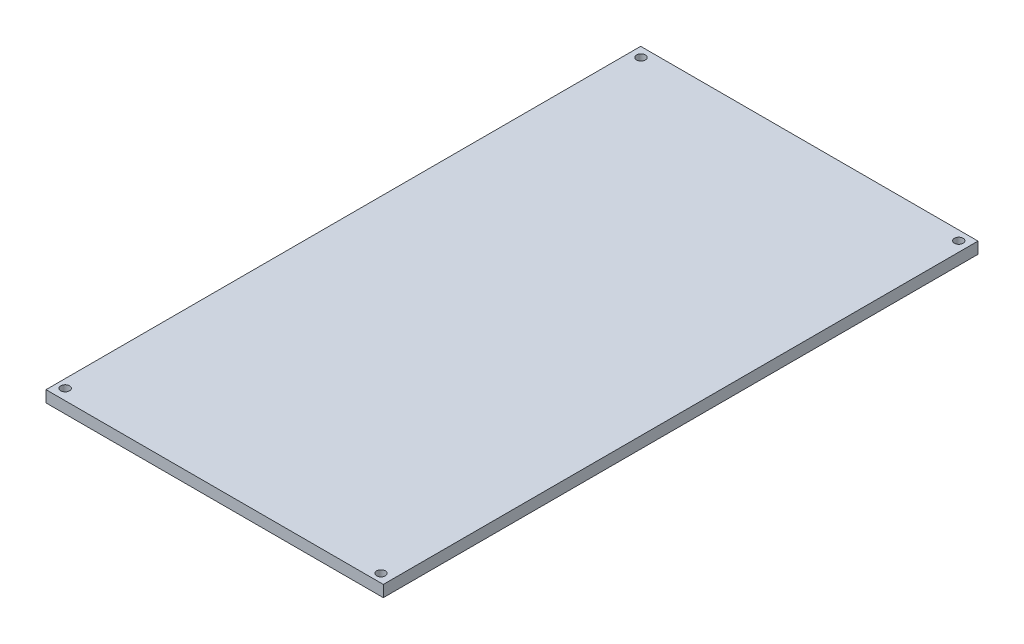
SolidWorks part; units mm, degrees
ref_plane "Front Plane" through (0, 0, 0) normal (0, 0, 1) x (1, 0, 0)
ref_plane "Top Plane" through (0, 0, 0) normal (0, 1, 0) x (1, 0, 0)
ref_plane "Right Plane" through (0, 0, 0) normal (1, 0, 0) x (0, 0, -1)
sketch "Sketch1" plane through (0, 0, 0) normal (0, 1, 0) x (1, 0, 0)
  line L1 (43.942, -77.47) -> (-43.942, -77.47)
  line L2 (43.942, -77.47) -> (43.942, 77.47)
  line L3 (43.942, 77.47) -> (-43.942, 77.47)
  line L4 (-43.942, -77.47) -> (-43.942, 77.47)
  line L5 (43.942, -77.47) -> (-43.942, 77.47) construction
  line L6 (43.942, 77.47) -> (-43.942, -77.47) construction
  circle A0 centre (41.3572, 75.0278) radius 1.143
  circle A1 centre (41.1446, -75.2747) radius 1.143
  circle A2 centre (-41.75, -74.6699) radius 1.143
  circle A3 centre (-41.3885, 74.9951) radius 1.143
  point P0 (0, 0)
  dimension "D3" = 2.286
  dimension "D5" = 2.286
  dimension "D7" = 2.286
  dimension "D9" = 2.286
  dimension "D1" = 87.884
  dimension "D2" = 154.94
  dimension "D4" = 3.556
  dimension "D6" = 3.556
  dimension "D8" = 3.556
  dimension "D10" = 3.556
extrude "Boss-Extrude2" add sketch "Sketch1" along normal blind 3 contours L1 L4 L3 L2
